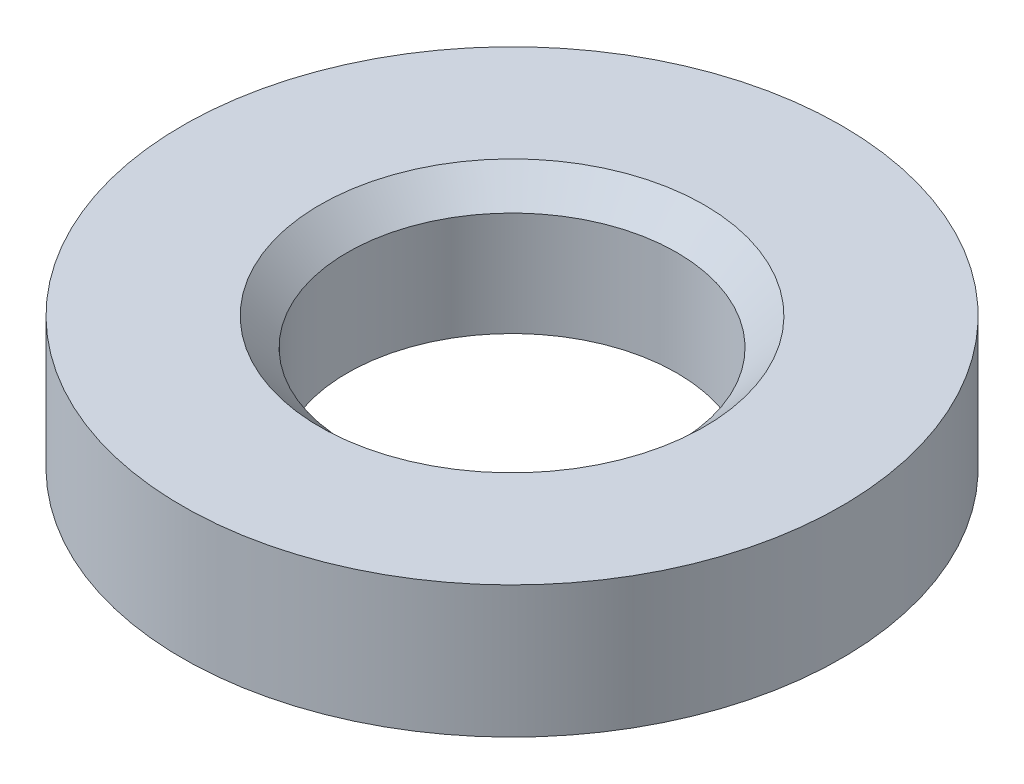
SolidWorks part; units mm, degrees
material "Простая углеродистая сталь"
ref_plane "Спереди" through (0, 0, 0) normal (0, 0, 1) x (1, 0, 0)
ref_plane "Сверху" through (0, 0, 0) normal (0, 1, 0) x (1, 0, 0)
ref_plane "Справа" through (0, 0, 0) normal (1, 0, 0) x (0, 0, -1)
sketch "Эскиз1" plane through (0, 0, 0) normal (0, 0, 1) x (1, 0, 0)
  line L0 (30, 12) -> (17.5, 12)
  line L1 (17.5, 12) -> (15, 9.5)
  line L2 (15, 9.5) -> (15, 0)
  line L3 (15, 0) -> (30, 0)
  line L4 (30, 0) -> (30, 12)
  line L5 (0, 12) -> (0, 0) construction
revolve "Повернуть1" add sketch "Эскиз1" angle 360 about L5
